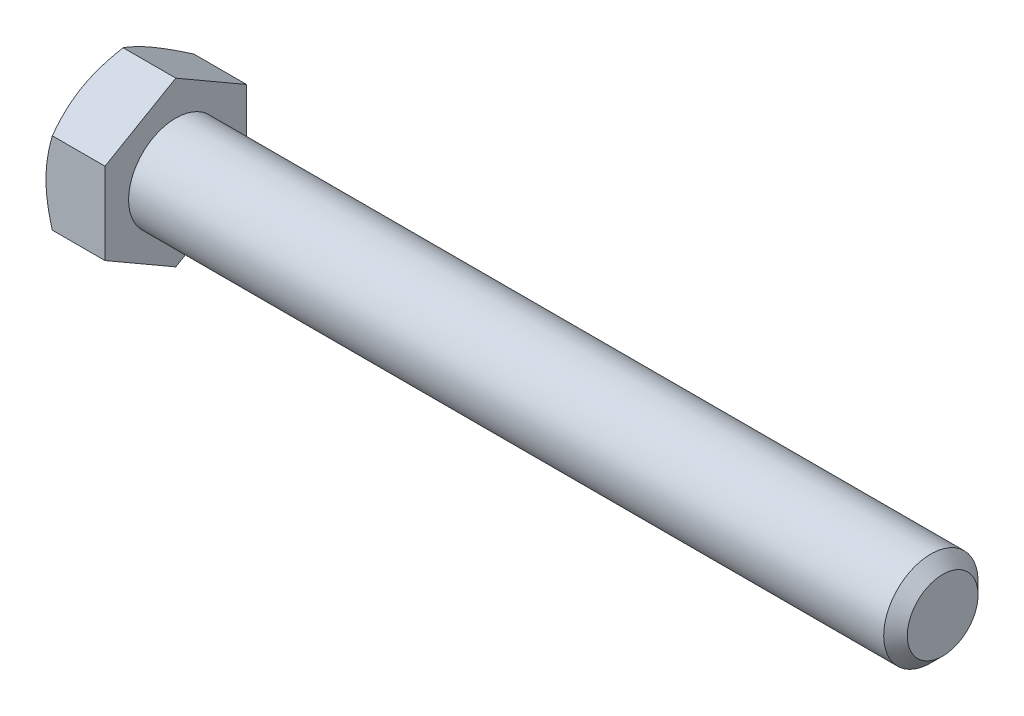
SolidWorks part; units mm, degrees
extrude "BaseHead" add sketch "HeadSke" along normal blind 5
sketch "HeadSke" plane through (0, 0, 0) normal (1, 0, 0) x (0, 0, -1)
  line L0 (6, 3.4641) -> (6, -3.4641)
  line L1 (-6, 3.4641) -> (-6, -3.4641)
  line L2 (6, -3.4641) -> (0, -6.9282)
  line L3 (0, -6.9282) -> (-6, -3.4641)
  line L4 (6, 3.4641) -> (0, 6.9282)
  line L5 (0, 6.9282) -> (-6, 3.4641)
  line L6 (0, 6.9282) -> (0, -6.9282) construction
  dimension "Width_flats" = 12
  dimension "D2" = 120
ref_plane "Plane1" through (0, 0, 0) normal (0, 0, 1) x (1, 0, 0)
ref_plane "Plane2" through (0, 0, 0) normal (0, 1, 0) x (1, 0, 0)
ref_plane "Plane3" through (0, 0, 0) normal (1, 0, 0) x (0, 0, -1)
other "Configuration Table"
sketch "BodySke" plane through (0, 0, 0) normal (0, 0, 1) x (1, 0, 0)
  line L0 (0, 3.4641) -> (0, -3.4641) construction
  line L1 (0, 0) -> (70, 0)
  line L2 (0, 0) -> (0, 4)
  line L3 (0, 4) -> (69, 4)
  line L4 (70, 0) -> (70, 3)
  line L5 (5, 6.9282) -> (5, 3.4641) construction
  line L6 (70, 3) -> (69, 4)
  line L7 (0, 0) -> (96.52, 0) construction
  line L8 (70, -3) -> (69, -4) construction
  line L9 (0, -4) -> (69, -4) construction
  line L10 (6.5, 15.24) -> (6.5, -1.27) construction
  line L11 (15, 6.8002) -> (15, -5.502) construction
  line L12 (5, 3.4641) -> (5, -3.4641) construction
  dimension "Thread_nom" = 55
revolve "BaseBody" add sketch "BodySke" angle 360 about L7
cosmetic thread "ThreadCosmetic" parameters "Thread_length"=55, "Thread_minor"=6
sketch "Sketch3" plane through (0, 0, 0) normal (0, 1, 0) x (1, 0, 0)
  line L0 (1.5, 8.5981) -> (-1.5, 3.4019)
  line L1 (1.5, 8.5981) -> (-10.5548, 15.5579)
  line L2 (-1.5, 3.4019) -> (-13.5548, 10.3617)
  line L3 (-10.5548, 15.5579) -> (-13.5548, 10.3617)
  line L4 (0, 6) -> (0, 0) construction
  line L6 (0, 0) -> (99.06, 0) construction
  dimension "D1" = 13.9196
  dimension "Head_ch_ang" = 30
revolve "HeadChamfer" cut sketch "Sketch3" angle 360 about L6
sketch "BearingSke" plane through (0, 0, 0) normal (0, 0, 1) x (1, 0, 0)
  line L0 (5, 6.9282) -> (0.5359, 6.9282) construction
  line L1 (5, 6.9282) -> (5, 3.4641) construction
  line L2 (5, 15) -> (4.2, 15)
  line L3 (5, 15) -> (5, 6.9282)
  line L4 (5, 6.9282) -> (4.2, 6.9282)
  line L5 (0, 0) -> (95.25, 0) construction
  line L6 (0, 0) -> (96.52, 0) construction
  line L7 (4.2, 15) -> (4.2, 6.9282)
  dimension "Bearing_ht" = 0.8
  dimension "Bearing_dia" = 30
revolve "BearingFace" cut sketch "BearingSke" angle 360 about L5
fillet "HeadFillet" [suppressed] radius 0.8
sketch "ThdSchSke" plane through (0, 0, 0) normal (0, 0, 1) x (1, 0, 0)
  line L0 (15, -3) -> (14.2998, -4)
  line L1 (15, -3) -> (15.7002, -4)
  line L2 (15.7002, -4) -> (15.7002, -5)
  line L3 (-3.175, 0) -> (5.1513, 0) construction
  line L5 (15.7002, -5) -> (14.2998, -5)
  line L6 (14.2998, -5) -> (14.2998, -4)
revolve "ThreadSchematic" [suppressed] cut sketch "ThdSchSke" angle 360 about L3
pattern_linear "ThdSchPat" [suppressed]
equation "\"Thread_minor@ThreadCosmetic\" = \"Minor_dia@BodySke\""
equation "\"Thread_length@ThreadCosmetic\" = ((sgn( (\"Length@BodySke\" - \"Advance@BodySke\" * 2.0 ) - \"Thread_nom@BodySke\" )-1)*( (\"Length@BodySke\" - \"Advance@BodySke\" * 2.0 ) - \"Thread_nom@BodySke\" ))/-2+ \"Thread_nom@BodySke\""
equation "\"Thread_minor@ThdSchSke\" = \"Minor_dia@BodySke\""
equation "\"Diameter@ThdSchSke\" = \"Diameter@BodySke\""
equation "\"Overcut@ThdSchSke\" = \"Diameter@BodySke\" * 1.25"
equation "\"Start@ThdSchSke\" = \"Head_ht@BaseHead\" + \"Length@BodySke\" - \"Thread_length@ThreadCosmetic\"  '---Non-countersunk---"
equation "\"Num_threads@ThdSchPat\" = int( \"Thread_length@ThreadCosmetic\" / \"Advance@BodySke\" + 0.999 )  + 1"
equation "\"Advance@ThdSchPat\" = \"Thread_length@ThreadCosmetic\" /  (\"Num_threads@ThdSchPat\" - 1) 'relax it"
equation "\"Num_threads@ThdSchPat\" = \"Num_threads@ThdSchPat\" - sgn( \"Num_threads@ThdSchPat\" - 1) '---chamfered tips only---"
